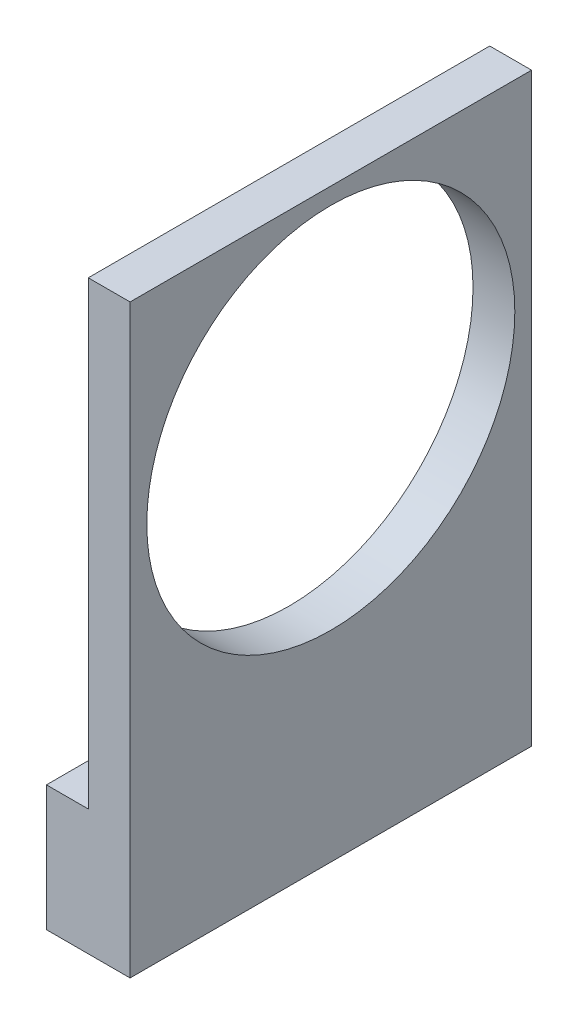
SolidWorks part; units mm, degrees
material "6061-T6 (SS)"
ref_plane "Front Plane" through (0, 0, 0) normal (0, 0, 1) x (1, 0, 0)
ref_plane "Top Plane" through (0, 0, 0) normal (0, 1, 0) x (1, 0, 0)
ref_plane "Right Plane" through (0, 0, 0) normal (1, 0, 0) x (0, 0, -1)
sketch "Sketch4" plane through (0, 0, 0) normal (1, 0, 0) x (0, 0, -1)
  line L1 (24, 35) -> (-24, 35)
  line L2 (24, 35) -> (24, -35)
  line L3 (24, -35) -> (-24, -35)
  line L4 (-24, 35) -> (-24, -35)
  line L5 (24, 35) -> (-24, -35) construction
  line L6 (24, -35) -> (-24, 35) construction
  circle A0 centre (0, 11) radius 22
  point P0 (0, 0)
  dimension "D3" = 44
  dimension "D1" = 70
  dimension "D2" = 48
  dimension "D4" = 24
extrude "Boss-Extrude2" add sketch "Sketch4" along normal blind 10
sketch "Sketch5" plane through (0, 0, -24) normal (0, 0, -1) x (-1, 0, 0)
  line L0 (-10, 35) -> (0, 35) construction
  line L1 (0, 35) -> (-5, 35)
  line L2 (0, 35) -> (0, -20)
  line L3 (0, -20) -> (-5, -20)
  line L4 (-5, 35) -> (-5, -20)
  dimension "D1" = 15
extrude "Cut-Extrude1" cut sketch "Sketch5" against normal through all
hole_wizard "Tap Drill for M4x0.7 Tap1" positions "Sketch6" profile "Sketch7" hole size "M4x0.7" standard "ANSI Metric"
sketch "Sketch6" plane through (0, -35, 0) normal (0, -1, 0) x (-1, 0, 0)
  line L3 (0, -24) -> (0, 24) construction
  line L4 (-10, 24) -> (0, 24) construction
  line L6 (-10, -24) -> (0, -24) construction
  point P0 (-5, 19)
  point P2 (-5, -19)
  dimension "D1" = 5
  dimension "D2" = 5
  dimension "D3" = 5
sketch "Sketch7" plane through (5, -35, -19) normal (1, 0, 0) x (0, 0, -1)
  line L0 (0, 0) -> (0, 10.9914)
  line L1 (0, 10.9914) -> (1.65, 10)
  line L2 (1.65, 10) -> (1.65, 0)
  line L5 (1.65, 0) -> (0, 0)
  line L10 (0, 10.9914) -> (-1.65, 10) construction
  line L11 (0, -6.35) -> (0, 107.95) construction
  dimension "Hole Dia." = 3.3
  dimension "Hole Depth" = 10
  dimension "Drill Angle" = 118
